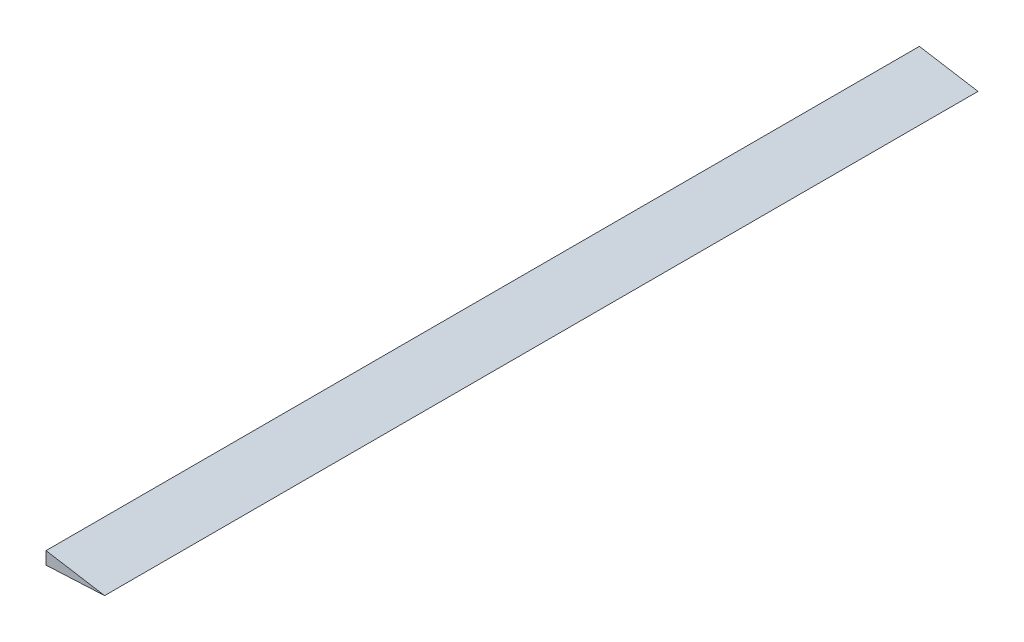
SolidWorks part; units mm, degrees
material "Balsa"
ref_plane "Front Plane" through (0, 0, 0) normal (0, 0, 1) x (1, 0, 0)
ref_plane "Top Plane" through (0, 0, 0) normal (0, 1, 0) x (1, 0, 0)
ref_plane "Right Plane" through (0, 0, 0) normal (1, 0, 0) x (0, 0, -1)
sketch "Sketch1" plane through (0, 0, 0) normal (0, 0, 1) x (1, 0, 0)
  line L0 (274.1027, -2.5258) -> (274.1027, 8.3995) construction
  line L1 (274.1027, -2.5258) -> (274.1027, 8.3995)
  line L2 (274.1027, 8.3995) -> (324.9027, 0)
  line L3 (274.1027, -2.5258) -> (324.9027, 0)
  spline S0 degree 3 poles (322.4569, 0.0391) (325.5224, -0.0392) (322.494, 0.2669) (320.1071, 0.7289) (314.4799, 1.6966) (307.762, 2.9665) (299.1562, 4.444) (289.109, 6.0546) (277.6145, 7.8586) (264.868, 9.8286) (251.0379, 11.9465) (236.3205, 14.1628) (220.9155, 16.4348) (205.0337, 18.7163) (188.8833, 20.923) (172.6824, 22.9973) (156.6226, 24.8302) (140.8504, 26.2626) (125.4788, 27.205) (110.5966, 27.6094) (96.2853, 27.4447) (82.6165, 26.7222) (69.6684, 25.4643) (57.5289, 23.7891) (46.3057, 21.7558) (36.1125, 19.4216) (27.0455, 16.847) (19.197, 14.0824) (12.6195, 11.1953) (7.3938, 8.2736) (3.4665, 5.3626) (1.0721, 2.6975) (-0.443, -0.0164) (1.1421, -2.6604) (4.365, -4.2268) (8.9712, -6.0288) (15.2436, -7.4956) (23.0321, -8.8134) (32.3248, -9.885) (43.0256, -10.722) (55.037, -11.3213) (68.2344, -11.6831) (82.4769, -11.8217) (97.6059, -11.7313) (113.4687, -11.4146) (129.93, -10.7985) (146.8597, -9.9388) (164.1026, -8.9547) (181.4553, -7.9142) (198.6946, -6.861) (215.5964, -5.837) (231.9426, -4.8635) (247.5179, -3.9672) (262.1184, -3.1571) (275.5429, -2.4457) (287.6227, -1.8357) (298.159, -1.3068) (307.1654, -0.8268) (314.174, -0.3689) (319.9998, -0.1172) (322.4569, 0.0391) (325.5224, -0.0392) (322.494, 0.2669) knots -0.015092 -0.006889 -0.001754 0 0.001748 0.006827 0.01488 0.025572 0.038694 0.054171 0.071834 0.091435 0.112685 0.135293 0.158944 0.183315 0.20807 0.232879 0.257399 0.281384 0.304706 0.327241 0.348897 0.369607 0.389308 0.407886 0.425177 0.441027 0.4553 0.467904 0.478752 0.487814 0.49509 0.500617 0.504451 0.507804 0.513091 0.520546 0.530249 0.542214 0.556382 0.572656 0.590895 0.610925 0.632536 0.655496 0.679547 0.704499 0.730211 0.756436 0.782837 0.809062 0.834776 0.859641 0.883338 0.905541 0.925965 0.944326 0.960366 0.973929 0.984908 0.993111 0.998246 1 1.001748 1.006827 1.01488 only from (324.9027, 0) to (324.9027, 0) construction
  spline S1 degree 3 poles (322.4569, 0.0391) (325.5224, -0.0392) (322.494, 0.2669) (320.1071, 0.7289) (314.4799, 1.6966) (307.762, 2.9665) (299.1562, 4.444) (289.109, 6.0546) (277.6145, 7.8586) (264.868, 9.8286) (251.0379, 11.9465) (236.3205, 14.1628) (220.9155, 16.4348) (205.0337, 18.7163) (188.8833, 20.923) (172.6824, 22.9973) (156.6226, 24.8302) (140.8504, 26.2626) (125.4788, 27.205) (110.5966, 27.6094) (96.2853, 27.4447) (82.6165, 26.7222) (69.6684, 25.4643) (57.5289, 23.7891) (46.3057, 21.7558) (36.1125, 19.4216) (27.0455, 16.847) (19.197, 14.0824) (12.6195, 11.1953) (7.3938, 8.2736) (3.4665, 5.3626) (1.0721, 2.6975) (-0.443, -0.0164) (1.1421, -2.6604) (4.365, -4.2268) (8.9712, -6.0288) (15.2436, -7.4956) (23.0321, -8.8134) (32.3248, -9.885) (43.0256, -10.722) (55.037, -11.3213) (68.2344, -11.6831) (82.4769, -11.8217) (97.6059, -11.7313) (113.4687, -11.4146) (129.93, -10.7985) (146.8597, -9.9388) (164.1026, -8.9547) (181.4553, -7.9142) (198.6946, -6.861) (215.5964, -5.837) (231.9426, -4.8635) (247.5179, -3.9672) (262.1184, -3.1571) (275.5429, -2.4457) (287.6227, -1.8357) (298.159, -1.3068) (307.1654, -0.8268) (314.174, -0.3689) (319.9998, -0.1172) (322.4569, 0.0391) (325.5224, -0.0392) (322.494, 0.2669) knots -0.015092 -0.006889 -0.001754 0 0.001748 0.006827 0.01488 0.025572 0.038694 0.054171 0.071834 0.091435 0.112685 0.135293 0.158944 0.183315 0.20807 0.232879 0.257399 0.281384 0.304706 0.327241 0.348897 0.369607 0.389308 0.407886 0.425177 0.441027 0.4553 0.467904 0.478752 0.487814 0.49509 0.500617 0.504451 0.507804 0.513091 0.520546 0.530249 0.542214 0.556382 0.572656 0.590895 0.610925 0.632536 0.655496 0.679547 0.704499 0.730211 0.756436 0.782837 0.809062 0.834776 0.859641 0.883338 0.905541 0.925965 0.944326 0.960366 0.973929 0.984908 0.993111 0.998246 1 1.001748 1.006827 1.01488 only from (324.9027, 0) to (324.9027, 0)
sketch "Sketch2" plane through (0, 0, -761.9997) normal (0, 0, -1) x (-1, 0, 0)
  line L0 (-274.1027, -2.5258) -> (-274.1027, 8.3995) construction
  line L1 (-274.1027, -2.5258) -> (-324.9027, 0) construction
  line L2 (-274.1027, 8.3995) -> (-324.9027, 0) construction
  line L3 (-274.1027, -2.5258) -> (-274.1027, 8.3995)
  line L4 (-274.1027, -2.5258) -> (-324.9027, 0)
  line L5 (-274.1027, 8.3995) -> (-324.9027, 0)
extrude "Boss-Extrude2" add sketch "Sketch2" against normal up to surface (756.9197 mm away)
